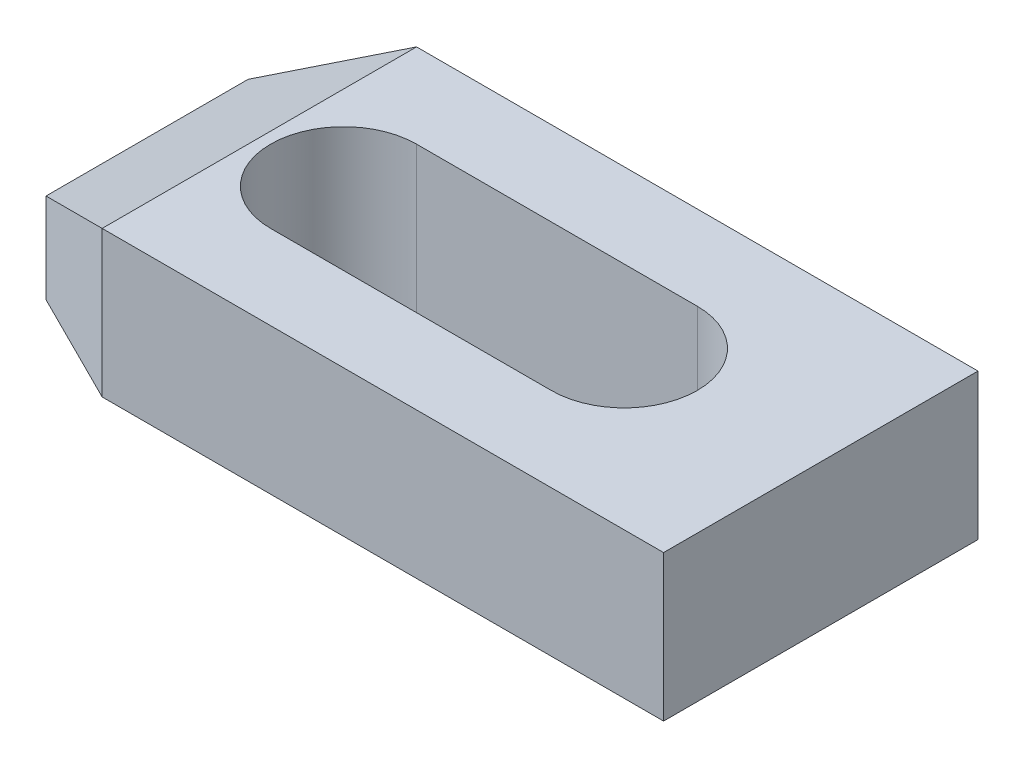
SolidWorks part; units mm, degrees
ref_plane "Front Plane" through (0, 0, 0) normal (0, 0, 1) x (1, 0, 0)
ref_plane "Top Plane" through (0, 0, 0) normal (0, 1, 0) x (1, 0, 0)
ref_plane "Right Plane" through (0, 0, 0) normal (1, 0, 0) x (0, 0, -1)
sketch "Sketch1" plane through (0, 0, 0) normal (0, 1, 0) x (1, 0, 0)
  line L0 (-12.5, 0) -> (12.5, 0) construction
  line L1 (-20, -14) -> (30, -14)
  line L2 (-30, -9) -> (-30, 9)
  line L3 (-20, 14) -> (30, 14)
  line L4 (30, -14) -> (30, 14)
  line L5 (-30, -14) -> (30, 14) construction
  line L6 (-30, 14) -> (30, -14) construction
  line L7 (-12.5, 6.5) -> (12.5, 6.5)
  line L8 (-12.5, -6.5) -> (12.5, -6.5)
  line L9 (-20, 14) -> (-20, -14) construction
  line L10 (-20, -14) -> (-30, -9)
  line L11 (-20, 14) -> (-30, 9)
  line L12 (-20, 14) -> (-30, 14) construction
  line L13 (-30, 14) -> (-30, 9) construction
  line L14 (-30, -9) -> (-30, -14) construction
  line L15 (-30, -14) -> (-20, -14) construction
  arc A0 (-12.5, 6.5) -> (-12.5, -6.5) centre (-12.5, 0) ccw
  arc A1 (12.5, -6.5) -> (12.5, 6.5) centre (12.5, 0) ccw
  point P0 (0, 0)
  point P8 (0, 0)
  dimension "D1" = 60
  dimension "D2" = 28
  dimension "D3" = 13
  dimension "D4" = 25
  dimension "D5" = 10
  dimension "D6" = 5
extrude "Boss-Extrude1" add sketch "Sketch1" along normal blind 13
sketch "Sketch2" plane through (0, 0, 14) normal (0, 0, 1) x (1, 0, 0)
  line L0 (-30, 13) -> (-20, 13)
  line L1 (-20, 13) -> (30, 13) construction
  line L2 (-20, 13) -> (-30, 8)
  line L3 (-30, 13) -> (-30, 0) construction
  line L4 (-30, 8) -> (-30, 13)
  dimension "D1" = 10
  dimension "D2" = 5
extrude "Cut-Extrude1" cut sketch "Sketch2" against normal through all
